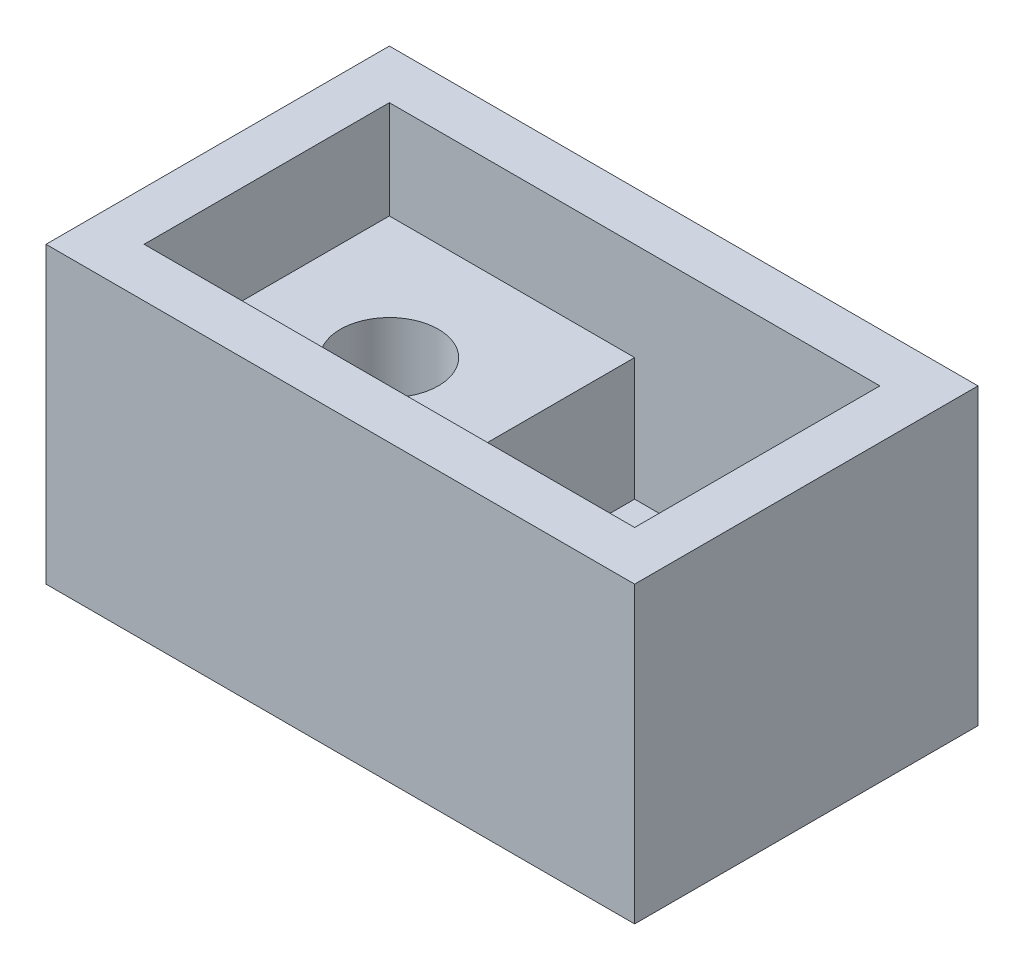
SolidWorks part; units mm, degrees
ref_plane "Front Plane" through (0, 0, 0) normal (0, 0, 1) x (1, 0, 0)
ref_plane "Top Plane" through (0, 0, 0) normal (0, 1, 0) x (1, 0, 0)
ref_plane "Right Plane" through (0, 0, 0) normal (1, 0, 0) x (0, 0, -1)
sketch "Sketch1" plane through (0, 0, 0) normal (0, 1, 0) x (1, 0, 0)
  line L0 (0, 177.8) -> (304.8, 177.8)
  line L1 (0, 0) -> (304.8, 0)
  line L2 (0, 0) -> (0, 177.8)
  line L4 (304.8, 0) -> (304.8, 177.8)
  line L6 (25.4, 152.4) -> (279.4, 152.4)
  line L7 (25.4, 152.4) -> (25.4, 25.4)
  line L8 (25.4, 25.4) -> (279.4, 25.4)
  line L9 (279.4, 152.4) -> (279.4, 25.4)
  line L10 (152.4, 152.4) -> (152.4, 25.4)
  circle A0 centre (88.9, 88.9) radius 25.4
  circle A1 centre (215.9, 88.9) radius 25.4
  dimension "D1" = 304.8
  dimension "D2" = 177.8
  dimension "D3" = 25.4
  dimension "D4" = 25.4
  dimension "D5" = 25.4
  dimension "D6" = 25.4
  dimension "D7" = 88.9
  dimension "D8" = 88.9
sketch "Sketch3" plane through (0, 0, 0) normal (0, 1, 0) x (1, 0, 0)
  line L0 (152.4, 152.4) -> (152.4, 25.4)
  line L5 (25.4, 152.4) -> (279.4, 152.4)
  line L6 (25.4, 152.4) -> (25.4, 25.4)
  line L7 (25.4, 25.4) -> (279.4, 25.4)
  line L8 (279.4, 152.4) -> (279.4, 25.4)
  circle A0 centre (88.9, 88.9) radius 25.4
  circle A1 centre (215.9, 88.9) radius 25.4
  point P4 (0, 0)
extrude "Boss-Extrude2" add sketch "Sketch1" against normal blind 152.4 contours L1 L4 L0 L2 L6 L9 L8 L7
sketch "Sketch4" plane through (0, 0, 0) normal (0, 1, 0) x (1, 0, 0)
  line L0 (152.4, 152.4) -> (152.4, 25.4)
  line L1 (25.4, 152.4) -> (279.4, 152.4)
  line L2 (25.4, 152.4) -> (25.4, 25.4)
  line L3 (25.4, 25.4) -> (279.4, 25.4)
  line L4 (279.4, 152.4) -> (279.4, 25.4)
  line L6 (0, 177.8) -> (304.8, 177.8)
  line L7 (0, 177.8) -> (0, 0)
  line L8 (0, 0) -> (304.8, 0)
  line L9 (304.8, 177.8) -> (304.8, 0)
  line L10 (25.4, 25.4) -> (279.4, 25.4)
  line L11 (25.4, 25.4) -> (25.4, 152.4)
  line L12 (25.4, 152.4) -> (279.4, 152.4)
  line L13 (279.4, 25.4) -> (279.4, 152.4)
  circle A0 centre (88.9, 88.9) radius 25.4
  circle A1 centre (215.9, 88.9) radius 25.4
extrude "Boss-Extrude3" add sketch "Sketch4" against normal blind 152.4 contours L4 L1 L0 L3 A1 | L2 L3 L0 L1 A0
sketch "Sketch5" plane through (0, 0, 0) normal (0, 1, 0) x (1, 0, 0)
  line L1 (279.4, 152.4) -> (152.4, 152.4)
  line L2 (279.4, 152.4) -> (279.4, 25.4)
  line L3 (279.4, 25.4) -> (152.4, 25.4)
  line L4 (152.4, 152.4) -> (152.4, 25.4)
  line L5 (152.4, 152.4) -> (25.4, 152.4)
  line L6 (152.4, 152.4) -> (152.4, 25.4)
  line L7 (152.4, 25.4) -> (25.4, 25.4)
  line L8 (25.4, 152.4) -> (25.4, 25.4)
sketch "Sketch6" plane through (0, 0, 0) normal (0, 1, 0) x (1, 0, 0)
  line L1 (279.4, 152.4) -> (152.4, 152.4)
  line L2 (279.4, 152.4) -> (279.4, 25.4)
  line L3 (279.4, 25.4) -> (152.4, 25.4)
  line L4 (152.4, 152.4) -> (152.4, 25.4)
  line L5 (152.4, 152.4) -> (25.4, 152.4)
  line L6 (152.4, 152.4) -> (152.4, 25.4)
  line L7 (152.4, 25.4) -> (25.4, 25.4)
  line L8 (25.4, 152.4) -> (25.4, 25.4)
sketch "Sketch7" plane through (0, 0, 0) normal (0, 1, 0) x (1, 0, 0)
  line L1 (152.4, 152.4) -> (25.4, 152.4)
  line L2 (152.4, 152.4) -> (152.4, 25.4)
  line L3 (152.4, 25.4) -> (25.4, 25.4)
  line L4 (25.4, 152.4) -> (25.4, 25.4)
extrude "Cut-Extrude1" cut sketch "Sketch5" against normal blind 50.8 contours L5 L8 L7 L4
sketch "Sketch10" plane through (0, 0, 0) normal (0, 1, 0) x (1, 0, 0)
  line L1 (279.4, 152.4) -> (152.4, 152.4)
  line L2 (279.4, 152.4) -> (279.4, 25.4)
  line L3 (279.4, 25.4) -> (152.4, 25.4)
  line L4 (152.4, 152.4) -> (152.4, 25.4)
extrude "Cut-Extrude2" cut sketch "Sketch10" against normal blind 114.3
